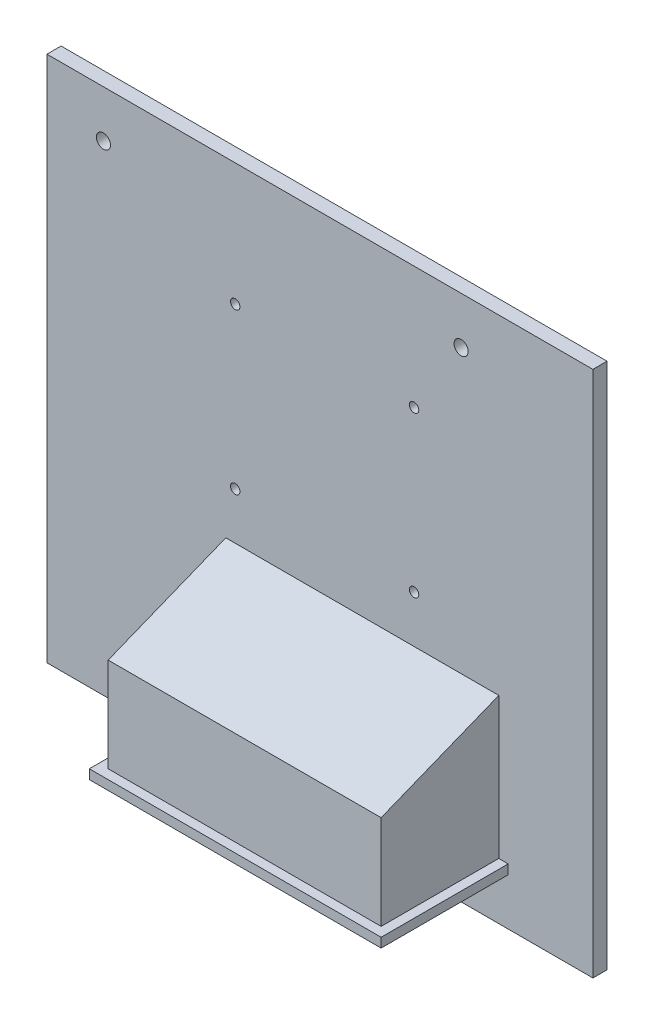
SolidWorks part; units mm, degrees
ref_plane "Alzado" through (0, 0, 0) normal (0, 0, 1) x (1, 0, 0)
ref_plane "Planta" through (0, 0, 0) normal (0, 1, 0) x (1, 0, 0)
ref_plane "Vista lateral" through (0, 0, 0) normal (1, 0, 0) x (0, 0, -1)
sketch "Croquis1" plane through (0, 0, 0) normal (0, 0, 1) x (1, 0, 0)
  line L1 (-58, -56) -> (58, -56)
  line L2 (-58, -56) -> (-58, 56)
  line L3 (-58, 56) -> (58, 56)
  line L4 (58, -56) -> (58, 56)
  line L5 (-58, -56) -> (58, 56) construction
  line L6 (-58, 56) -> (58, -56) construction
  point P0 (0, 0)
  dimension "D1" = 116
  dimension "D2" = 112
extrude "Saliente-Extruir1" add sketch "Croquis1" along normal blind 3
sketch "Croquis2" plane through (0, 0, 3) normal (0, 0, 1) x (1, 0, 0)
  line L0 (58, -56) -> (58, 56) construction
  line L1 (-20, -48) -> (38, -48)
  line L2 (-20, -48) -> (-20, -14)
  line L3 (-20, -14) -> (38, -14)
  line L4 (38, -48) -> (38, -14)
  line L5 (-20, -48) -> (38, -14) construction
  line L6 (-20, -14) -> (38, -48) construction
  line L7 (-58, -56) -> (58, -56) construction
  point P0 (9, -31)
  dimension "D1" = 20
  dimension "D2" = 8
  dimension "D3" = 34
  dimension "D4" = 58
extrude "Saliente-Extruir2" add sketch "Croquis2" along normal blind 25
ref_plane "Plano1" through (0, -46, 0) normal (0, -1, 0) x (-1, 0, 0)
sketch "Croquis3" plane through (0, -46, 0) normal (0, -1, 0) x (-1, 0, 0)
  line L0 (-40, -3) -> (-40, -30)
  line L1 (58, -3) -> (-58, -3) construction
  line L2 (-40, -30) -> (22, -30)
  line L3 (22, -30) -> (22, -3)
  line L4 (22, -3) -> (-40, -3)
  line L5 (-38, -28) -> (-38, -3) construction
  line L6 (20, -28) -> (20, -3) construction
  line L7 (20, -28) -> (-38, -28) construction
  dimension "D1" = 2
  dimension "D2" = 2
  dimension "D3" = 2
extrude "Saliente-Extruir3" add sketch "Croquis3" against normal blind 2
sketch "Croquis4" plane through (38, 0, 0) normal (1, 0, 0) x (0, 0, -1)
  line L0 (-3, -14) -> (-28, -24.0005)
  line L1 (-28, -44) -> (-28, -14) construction
  line L2 (-28, -24.0005) -> (-28, -14)
  line L3 (-28, -14) -> (-3, -14)
  dimension "D1" = 26.926
extrude "Cortar-Extruir1" cut sketch "Croquis4" against normal through all
sketch "Croquis5" plane through (0, 0, 3) normal (0, 0, 1) x (1, 0, 0)
  line L0 (-58, 56) -> (-58, -56) construction
  line L1 (-58, -56) -> (58, -56) construction
  line L2 (58, 56) -> (-58, 56) construction
  line L3 (38, -14) -> (-20, -14) construction
  line L4 (58, -56) -> (58, 56) construction
  circle A0 centre (-36, -46) radius 1.5
  circle A1 centre (-46, 46) radius 1.5
  circle A2 centre (30, 46) radius 1.5
  circle A3 centre (20, 30) radius 1
  circle A4 centre (20, -4) radius 1
  circle A5 centre (-18, -4) radius 1
  circle A6 centre (-18, 30) radius 1
  dimension "D1" = 3
  dimension "D2" = 22
  dimension "D3" = 10
  dimension "D4" = 3
  dimension "D5" = 10
  dimension "D6" = 12
  dimension "D8" = 2
  dimension "D12" = 34
  dimension "D13" = 10
  dimension "D14" = 38
  dimension "D7" = 76
  dimension "D9" = 38
  dimension "D10" = 38
  dimension "D11" = 34
  dimension "D15" = 38
  dimension "D16" = 10
extrude "Cortar-Extruir2" cut sketch "Croquis5" against normal through all
